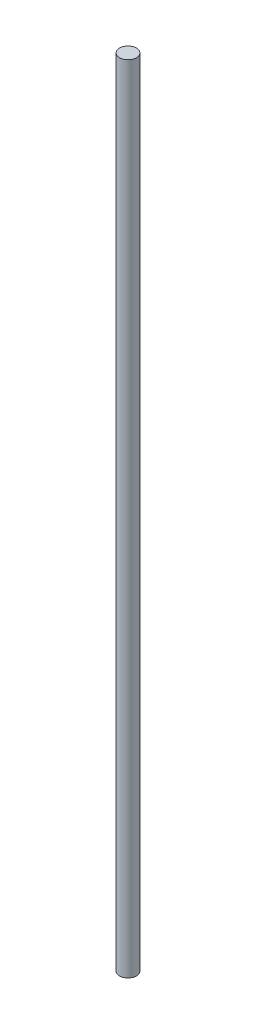
SolidWorks part; units mm, degrees
ref_plane "Alzado" through (0, 0, 0) normal (0, 0, 1) x (1, 0, 0)
ref_plane "Planta" through (0, 0, 0) normal (0, 1, 0) x (1, 0, 0)
ref_plane "Vista lateral" through (0, 0, 0) normal (1, 0, 0) x (0, 0, -1)
sketch "Croquis1" plane through (0, 0, 0) normal (0, 1, 0) x (1, 0, 0)
  circle A0 centre (-8.5683, 5.4182) radius 4
extrude "Saliente-Extruir1" add sketch "Croquis1" along normal blind 377.5
